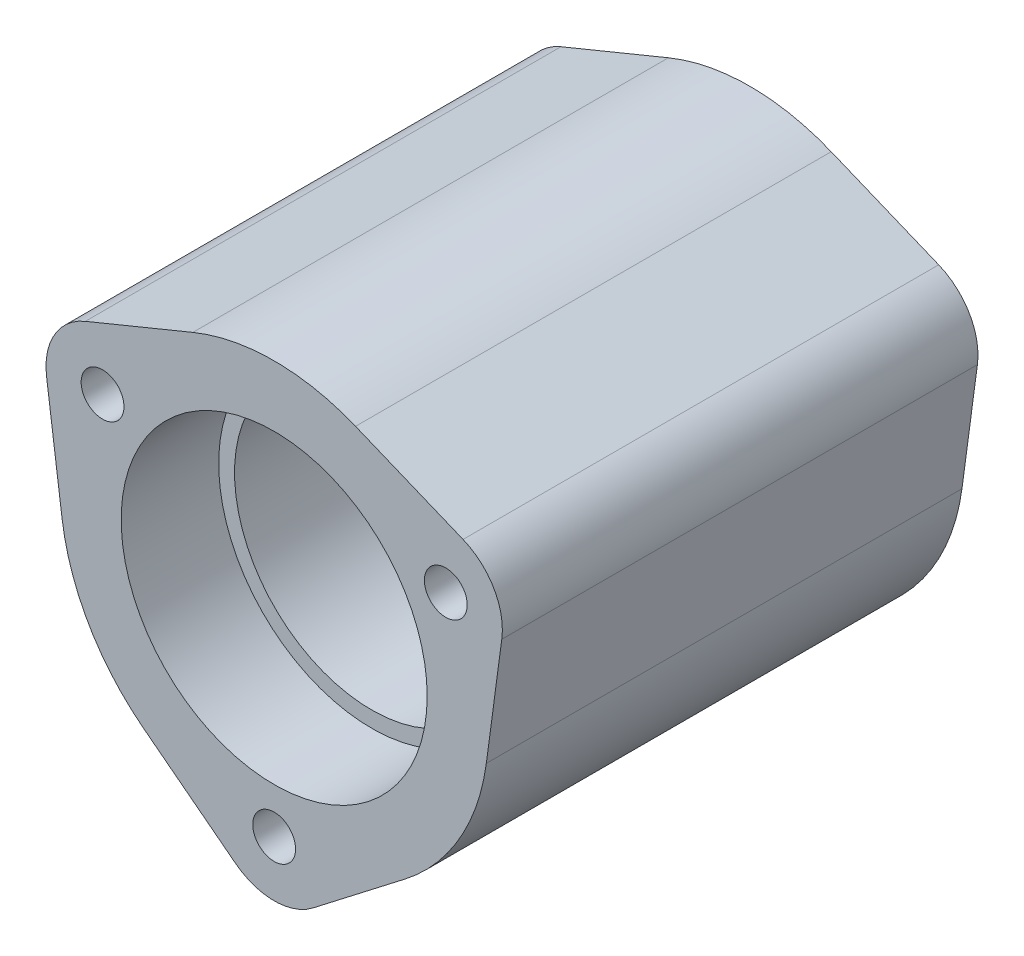
SolidWorks part; units mm, degrees
ref_plane "Спереди" through (0, 0, 0) normal (0, 0, 1) x (1, 0, 0)
ref_plane "Сверху" through (0, 0, 0) normal (0, 1, 0) x (1, 0, 0)
ref_plane "Справа" through (0, 0, 0) normal (1, 0, 0) x (0, 0, -1)
sketch "Эскиз1" plane through (0, 0, 0) normal (0, 0, 1) x (1, 0, 0)
  line L0 (-11.9128, 9.6997) -> (-5.1317, 12.4866)
  line L1 (0, 0) -> (0, -12) construction
  line L2 (-14.3566, 5.4669) -> (-13.3796, -1.7991)
  line L3 (2.4438, -15.1667) -> (8.2479, -10.6875)
  line L4 (-2.4438, -15.1667) -> (-8.2479, -10.6875)
  line L5 (14.3566, 5.4669) -> (13.3796, -1.7991)
  line L6 (11.9128, 9.6997) -> (5.1317, 12.4866)
  circle A0 centre (0, 0) radius 13.5 construction
  arc A1 (8.2479, -10.6875) -> (13.3796, -1.7991) centre (0, 0) ccw
  arc A2 (-11.9128, 9.6997) -> (-14.3566, 5.4669) centre (-10.3923, 6) ccw
  arc A3 (-2.4438, -15.1667) -> (2.4438, -15.1667) centre (0, -12) ccw
  arc A4 (14.3566, 5.4669) -> (11.9128, 9.6997) centre (10.3923, 6) ccw
  arc A5 (5.1317, 12.4866) -> (-5.1317, 12.4866) centre (0, 0) ccw
  arc A6 (-13.3796, -1.7991) -> (-8.2479, -10.6875) centre (0, 0) ccw
  circle A7 centre (0, 0) radius 12 construction
  point P24 (0, 0)
  dimension "D1" = 4
  dimension "D2" = 27
  dimension "D3" = 3
  dimension "D4" = 24
extrude "тело" add sketch "Эскиз1" along normal mid plane 30
sketch "Эскиз2" plane through (0, 0, 15) normal (0, 0, 1) x (1, 0, 0)
  circle A0 centre (0, 0) radius 9.65
  dimension "D1" = 19.3
extrude "углубление под подшипник" cut sketch "Эскиз2" against normal blind 6.15
mirror "Углубление под подшипник с обратной стороны" about plane through (0, 0, 0) normal (0, 0, 1) of "углубление под подшипник"
sketch "Эскиз3" plane through (0, 0, 8.85) normal (0, 0, 1) x (1, 0, 0)
  circle A0 centre (0, 0) radius 8.65
  circle A1 centre (0, 0) radius 9.65 construction
  dimension "D1" = 1
extrude "сквозное отверстие под ось" cut sketch "Эскиз3" against normal through all
sketch "Эскиз4" plane through (0, 0, 15) normal (0, 0, 1) x (1, 0, 0)
  line L0 (0, -15.35) -> (0, -9.65) construction
  circle A0 centre (-10.8253, 6.25) radius 1.35
  circle A1 centre (0, -12.5) radius 1.35
  circle A2 centre (10.8253, 6.25) radius 1.35
  circle A4 centre (0, 0) radius 9.65 construction
  circle A5 centre (0, 0) radius 12.5 construction
  point P8 (0, 0)
  point P9 (-0.2181, -11.4979)
  point P10 (0, 0)
  point P18 (0, -12.5)
  dimension "D1" = 2.7
  dimension "D3" = 25
  dimension "D2" = 3
extrude "отверстия для шурупов" cut sketch "Эскиз4" against normal blind 11
mirror "Отверстия для шурупов с другой стороны" about plane through (0, 0, 0) normal (0, 0, 1) of "отверстия для шурупов"
